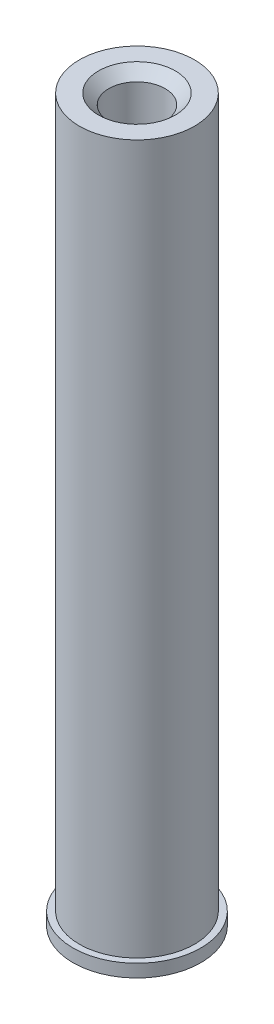
SolidWorks part; units mm, degrees
ref_plane "Front Plane" through (0, 0, 0) normal (0, 0, 1) x (1, 0, 0)
ref_plane "Top Plane" through (0, 0, 0) normal (0, 1, 0) x (1, 0, 0)
ref_plane "Right Plane" through (0, 0, 0) normal (1, 0, 0) x (0, 0, -1)
sketch "Sketch1" plane through (0, 0, 0) normal (0, 1, 0) x (1, 0, 0)
  circle A0 centre (0, 0) radius 2.5
  dimension "D1" = 5
extrude "Boss-Extrude1" add sketch "Sketch1" along normal blind 0.5
sketch "Sketch2" plane through (0, 0.5, 0) normal (0, 1, 0) x (1, 0, 0)
  circle A0 centre (0, 0) radius 2.25
  dimension "D1" = 4.5
extrude "Boss-Extrude2" add sketch "Sketch2" along normal blind 27.7
hole_wizard "CSK for M2 Countersunk Flat Head Screw1" positions "Sketch3" profile "Sketch4" countersink size "M2" standard "ISO"
sketch "Sketch3" plane through (0, 28.2, 0) normal (0, 1, 0) x (1, 0, 0)
  point P0 (0, 0)
sketch "Sketch4" plane through (0, 28.2, 0) normal (1, 0, 0) x (0, 0, 1)
  line L0 (0, 0) -> (0, 10)
  line L1 (0, 10) -> (1.1, 9.3391)
  line L2 (1.1, 9.3391) -> (1.1, 0.4)
  line L3 (1.1, 0.4) -> (1.5, 0)
  line L5 (1.5, 0) -> (0, 0)
  line L6 (-1.1, 0.4) -> (-1.5, 0) construction
  line L10 (0, 10) -> (-1.1, 9.3391) construction
  line L11 (0, -6.35) -> (0, 107.95) construction
  dimension "Hole Dia." = 2.2
  dimension "Hole Depth" = 10
  dimension "Near C'Sink Dia." = 3
  dimension "Near C'Sink Angle" = 90
  dimension "Drill Angle" = 118
